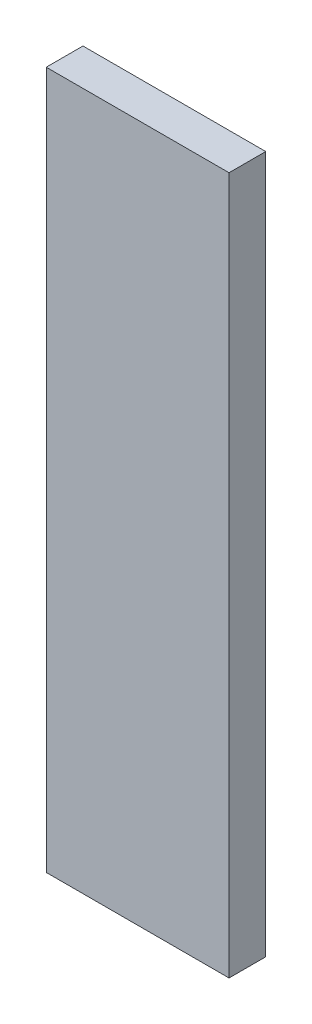
SolidWorks part; units mm, degrees
ref_plane "前视基准面" through (0, 0, 0) normal (0, 0, 1) x (1, 0, 0)
ref_plane "上视基准面" through (0, 0, 0) normal (0, 1, 0) x (1, 0, 0)
ref_plane "右视基准面" through (0, 0, 0) normal (1, 0, 0) x (0, 0, -1)
other "Configuration Table"
sketch "草图1" plane through (0, 0, 0) normal (0, 0, 1) x (1, 0, 0)
  line L1 (-24.9, 95) -> (24.9, 95)
  line L2 (-24.9, 95) -> (-24.9, -95)
  line L3 (-24.9, -95) -> (24.9, -95)
  line L4 (24.9, 95) -> (24.9, -95)
  line L5 (-24.9, 95) -> (24.9, -95) construction
  line L6 (-24.9, -95) -> (24.9, 95) construction
  point P0 (0, 0)
  dimension "D1" = 49.8
  dimension "D2" = 190
extrude "凸台-拉伸1" add sketch "草图1" along normal mid plane 10
sketch "草图3" plane through (0, -95, 0) normal (0, -1, 0) x (1, 0, 0)
  line L1 (-15.2, 3.15) -> (15.2, 3.15)
  line L2 (-15.2, 3.15) -> (-15.2, -3.15)
  line L3 (-15.2, -3.15) -> (15.2, -3.15)
  line L4 (15.2, 3.15) -> (15.2, -3.15)
  line L5 (-15.2, 3.15) -> (15.2, -3.15) construction
  line L6 (-15.2, -3.15) -> (15.2, 3.15) construction
  point P0 (0, 0)
  dimension "D1" = 6.3
  dimension "D2" = 30.4
extrude "切除-拉伸1" cut sketch "草图3" against normal blind 50
